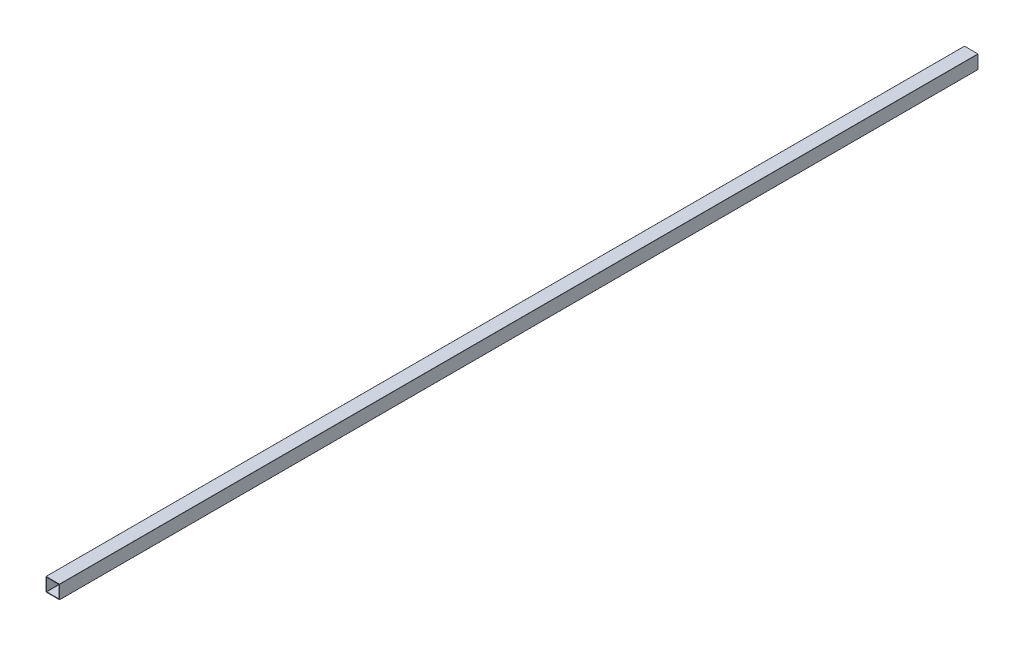
SolidWorks part; units mm, degrees
material "AISI 1035 Acero (SS)"
ref_plane "Alzado" through (0, 0, 0) normal (0, 0, 1) x (1, 0, 0)
ref_plane "Planta" through (0, 0, 0) normal (0, 1, 0) x (1, 0, 0)
ref_plane "Vista lateral" through (0, 0, 0) normal (1, 0, 0) x (0, 0, -1)
sketch "Croquis1" plane through (0, 0, 0) normal (0, 0, 1) x (1, 0, 0)
  line L0 (-40.65, -40.65) -> (-40.65, 40.65)
  line L1 (-44.45, -44.45) -> (44.45, -44.45)
  line L2 (-44.45, -44.45) -> (-44.45, 44.45)
  line L3 (-44.45, 44.45) -> (44.45, 44.45)
  line L4 (44.45, -44.45) -> (44.45, 44.45)
  line L5 (-44.45, -44.45) -> (44.45, 44.45) construction
  line L6 (-44.45, 44.45) -> (44.45, -44.45) construction
  line L7 (-40.65, 40.65) -> (40.65, 40.65)
  line L8 (40.65, -40.65) -> (40.65, 40.65)
  line L9 (-40.65, -40.65) -> (40.65, -40.65)
  point P0 (0, 0)
  dimension "D1" = 88.9
  dimension "D3" = 3.8
extrude "Saliente-Extruir1" add sketch "Croquis1" against normal blind 6000
fillet "Redondeo1" radius 1 8 edges at (-40.65, 40.65, -3000) (40.65, 40.65, -3000) (40.65, -40.65, -3000) (-44.45, -44.45, -3000) (-44.45, 44.45, -3000) (-40.65, -40.65, -3000) (44.45, -44.45, -3000) (44.45, 44.45, -3000)
